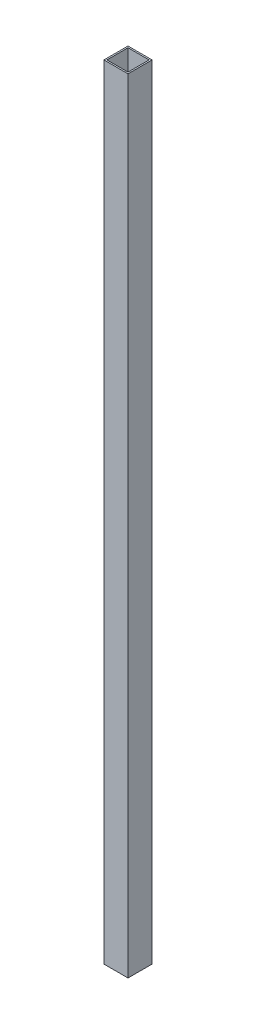
SolidWorks part; units mm, degrees
ref_plane "Front Plane" through (0, 0, 0) normal (0, 0, 1) x (1, 0, 0)
ref_plane "Top Plane" through (0, 0, 0) normal (0, 1, 0) x (1, 0, 0)
ref_plane "Right Plane" through (0, 0, 0) normal (1, 0, 0) x (0, 0, -1)
sketch "Sketch1" plane through (0, 0, 0) normal (0, 1, 0) x (1, 0, 0)
  line L1 (12.7, 12.7) -> (-12.7, 12.7)
  line L2 (12.7, 12.7) -> (12.7, -12.7)
  line L3 (12.7, -12.7) -> (-12.7, -12.7)
  line L4 (-12.7, 12.7) -> (-12.7, -12.7)
  line L5 (12.7, 12.7) -> (-12.7, -12.7) construction
  line L6 (12.7, -12.7) -> (-12.7, 12.7) construction
  line L7 (11.1125, 11.1125) -> (-11.1125, 11.1125)
  line L8 (11.1125, 11.1125) -> (11.1125, -11.1125)
  line L9 (11.1125, -11.1125) -> (-11.1125, -11.1125)
  line L10 (-11.1125, 11.1125) -> (-11.1125, -11.1125)
  line L11 (11.1125, 11.1125) -> (-11.1125, -11.1125) construction
  line L12 (11.1125, -11.1125) -> (-11.1125, 11.1125) construction
  point P1 (0, 0)
  point P6 (0, 0)
  dimension "D1" = 25.4
  dimension "D2" = 25.4
  dimension "D3" = 1.5875
  dimension "D4" = 1.5875
extrude "Boss-Extrude1" add sketch "Sketch1" along normal blind 825.5
